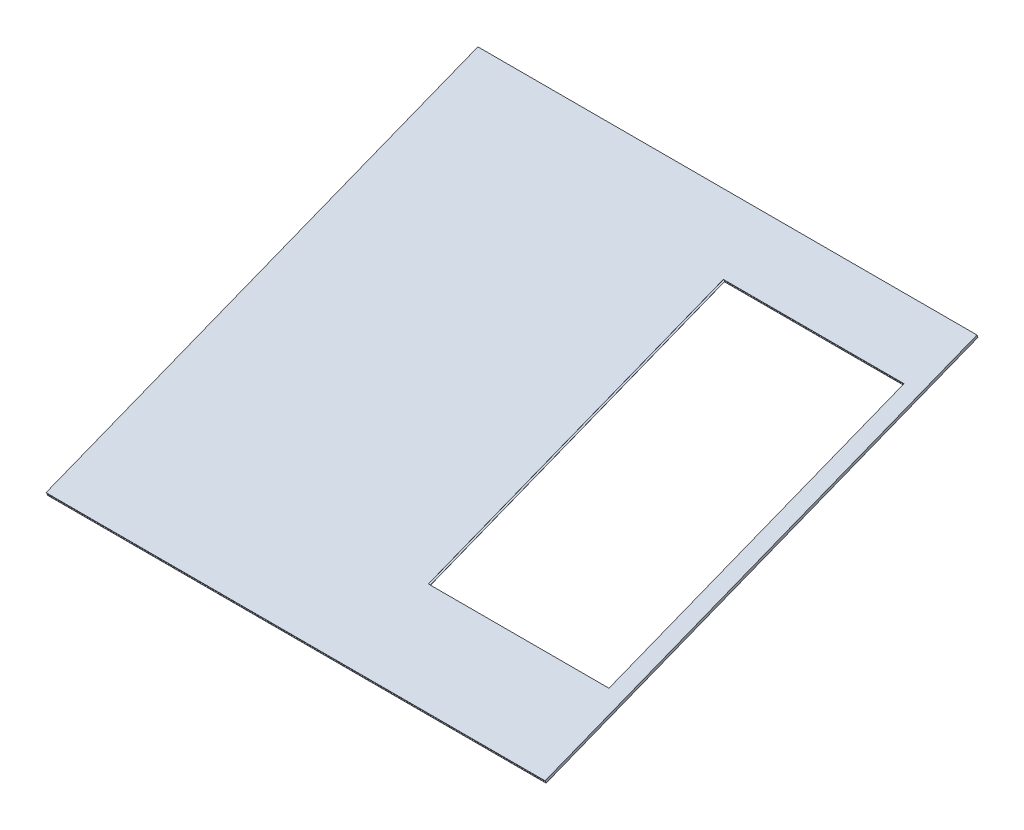
SolidWorks part; units mm, degrees
ref_plane "Front Plane" through (0, 0, 0) normal (0, 0, 1) x (1, 0, 0)
ref_plane "Top Plane" through (0, 0, 0) normal (0, 1, 0) x (1, 0, 0)
ref_plane "Right Plane" through (0, 0, 0) normal (1, 0, 0) x (0, 0, -1)
sketch "Sketch1" plane through (0, 0, 0) normal (1, 0, 0) x (0, 0, -1)
  line L0 (0, 0) -> (-1566.3458, 0) construction
  line L1 (0, 617) -> (-1566.3458, 0)
  line L2 (0, 0) -> (0, 617) construction
  dimension "D1" = 617
  dimension "D2" = 21.5
extrude "Extrude-Thin1" add sketch "Sketch1" along normal blind 1810 thin
sketch "Sketch2" plane through (0, 82.8774, -210.3965) normal (0, 0.3665, -0.9304) x (-1, 0, 0)
  line L0 (-1810, 584.0676) -> (-1810, 574.0676) construction
  line L1 (-1809.5, 583.5676) -> (-1800.5, 583.5676)
  line L2 (-1809.5, 583.5676) -> (-1809.5, 574.5676)
  line L3 (-1809.5, 574.5676) -> (-1800.5, 574.5676)
  line L4 (-1800.5, 583.5676) -> (-1800.5, 574.5676)
  line L5 (-1810, 584.0676) -> (0, 584.0676) construction
  line L6 (-1810, 574.0676) -> (0, 574.0676) construction
  line L7 (-1791, 583.5676) -> (-1791, 574.5676)
  line L8 (-1800, 574.5676) -> (-1791, 574.5676)
  line L9 (-1800, 583.5676) -> (-1800, 574.5676)
  line L10 (-1800, 583.5676) -> (-1791, 583.5676)
  line L11 (-1781.5, 583.5676) -> (-1781.5, 574.5676)
  line L12 (-1790.5, 574.5676) -> (-1781.5, 574.5676)
  line L13 (-1790.5, 583.5676) -> (-1790.5, 574.5676)
  line L14 (-1790.5, 583.5676) -> (-1781.5, 583.5676)
  line L15 (-1772, 583.5676) -> (-1772, 574.5676)
  line L16 (-1781, 574.5676) -> (-1772, 574.5676)
  line L17 (-1781, 583.5676) -> (-1781, 574.5676)
  line L18 (-1781, 583.5676) -> (-1772, 583.5676)
  line L19 (-1762.5, 583.5676) -> (-1762.5, 574.5676)
  line L20 (-1771.5, 574.5676) -> (-1762.5, 574.5676)
  line L21 (-1771.5, 583.5676) -> (-1771.5, 574.5676)
  line L22 (-1771.5, 583.5676) -> (-1762.5, 583.5676)
  line L23 (-1753, 583.5676) -> (-1753, 574.5676)
  line L24 (-1762, 574.5676) -> (-1753, 574.5676)
  line L25 (-1762, 583.5676) -> (-1762, 574.5676)
  line L26 (-1762, 583.5676) -> (-1753, 583.5676)
  line L27 (-1743.5, 583.5676) -> (-1743.5, 574.5676)
  line L28 (-1752.5, 574.5676) -> (-1743.5, 574.5676)
  line L29 (-1752.5, 583.5676) -> (-1752.5, 574.5676)
  line L30 (-1752.5, 583.5676) -> (-1743.5, 583.5676)
  line L31 (-1734, 583.5676) -> (-1734, 574.5676)
  line L32 (-1743, 574.5676) -> (-1734, 574.5676)
  line L33 (-1743, 583.5676) -> (-1743, 574.5676)
  line L34 (-1743, 583.5676) -> (-1734, 583.5676)
  line L35 (-1724.5, 583.5676) -> (-1724.5, 574.5676)
  line L36 (-1733.5, 574.5676) -> (-1724.5, 574.5676)
  line L37 (-1733.5, 583.5676) -> (-1733.5, 574.5676)
  line L38 (-1733.5, 583.5676) -> (-1724.5, 583.5676)
  line L39 (-1715, 583.5676) -> (-1715, 574.5676)
  line L40 (-1724, 574.5676) -> (-1715, 574.5676)
  line L41 (-1724, 583.5676) -> (-1724, 574.5676)
  line L42 (-1724, 583.5676) -> (-1715, 583.5676)
  line L43 (-1705.5, 583.5676) -> (-1705.5, 574.5676)
  line L44 (-1714.5, 574.5676) -> (-1705.5, 574.5676)
  line L45 (-1714.5, 583.5676) -> (-1714.5, 574.5676)
  line L46 (-1714.5, 583.5676) -> (-1705.5, 583.5676)
  line L47 (-1696, 583.5676) -> (-1696, 574.5676)
  line L48 (-1705, 574.5676) -> (-1696, 574.5676)
  line L49 (-1705, 583.5676) -> (-1705, 574.5676)
  line L50 (-1705, 583.5676) -> (-1696, 583.5676)
  line L51 (-1686.5, 583.5676) -> (-1686.5, 574.5676)
  line L52 (-1695.5, 574.5676) -> (-1686.5, 574.5676)
  line L53 (-1695.5, 583.5676) -> (-1695.5, 574.5676)
  line L54 (-1695.5, 583.5676) -> (-1686.5, 583.5676)
  line L55 (-1677, 583.5676) -> (-1677, 574.5676)
  line L56 (-1686, 574.5676) -> (-1677, 574.5676)
  line L57 (-1686, 583.5676) -> (-1686, 574.5676)
  line L58 (-1686, 583.5676) -> (-1677, 583.5676)
  line L59 (-1667.5, 583.5676) -> (-1667.5, 574.5676)
  line L60 (-1676.5, 574.5676) -> (-1667.5, 574.5676)
  line L61 (-1676.5, 583.5676) -> (-1676.5, 574.5676)
  line L62 (-1676.5, 583.5676) -> (-1667.5, 583.5676)
  line L63 (-1658, 583.5676) -> (-1658, 574.5676)
  line L64 (-1667, 574.5676) -> (-1658, 574.5676)
  line L65 (-1667, 583.5676) -> (-1667, 574.5676)
  line L66 (-1667, 583.5676) -> (-1658, 583.5676)
  line L67 (-1648.5, 583.5676) -> (-1648.5, 574.5676)
  line L68 (-1657.5, 574.5676) -> (-1648.5, 574.5676)
  line L69 (-1657.5, 583.5676) -> (-1657.5, 574.5676)
  line L70 (-1657.5, 583.5676) -> (-1648.5, 583.5676)
  line L71 (-1639, 583.5676) -> (-1639, 574.5676)
  line L72 (-1648, 574.5676) -> (-1639, 574.5676)
  line L73 (-1648, 583.5676) -> (-1648, 574.5676)
  line L74 (-1648, 583.5676) -> (-1639, 583.5676)
  line L75 (-1629.5, 583.5676) -> (-1629.5, 574.5676)
  line L76 (-1638.5, 574.5676) -> (-1629.5, 574.5676)
  line L77 (-1638.5, 583.5676) -> (-1638.5, 574.5676)
  line L78 (-1638.5, 583.5676) -> (-1629.5, 583.5676)
  line L79 (-1620, 583.5676) -> (-1620, 574.5676)
  line L80 (-1629, 574.5676) -> (-1620, 574.5676)
  line L81 (-1629, 583.5676) -> (-1629, 574.5676)
  line L82 (-1629, 583.5676) -> (-1620, 583.5676)
  line L83 (-1610.5, 583.5676) -> (-1610.5, 574.5676)
  line L84 (-1619.5, 574.5676) -> (-1610.5, 574.5676)
  line L85 (-1619.5, 583.5676) -> (-1619.5, 574.5676)
  line L86 (-1619.5, 583.5676) -> (-1610.5, 583.5676)
  line L87 (-1601, 583.5676) -> (-1601, 574.5676)
  line L88 (-1610, 574.5676) -> (-1601, 574.5676)
  line L89 (-1610, 583.5676) -> (-1610, 574.5676)
  line L90 (-1610, 583.5676) -> (-1601, 583.5676)
  line L91 (-1591.5, 583.5676) -> (-1591.5, 574.5676)
  line L92 (-1600.5, 574.5676) -> (-1591.5, 574.5676)
  line L93 (-1600.5, 583.5676) -> (-1600.5, 574.5676)
  line L94 (-1600.5, 583.5676) -> (-1591.5, 583.5676)
  line L95 (-1582, 583.5676) -> (-1582, 574.5676)
  line L96 (-1591, 574.5676) -> (-1582, 574.5676)
  line L97 (-1591, 583.5676) -> (-1591, 574.5676)
  line L98 (-1591, 583.5676) -> (-1582, 583.5676)
  line L99 (-1572.5, 583.5676) -> (-1572.5, 574.5676)
  line L100 (-1581.5, 574.5676) -> (-1572.5, 574.5676)
  line L101 (-1581.5, 583.5676) -> (-1581.5, 574.5676)
  line L102 (-1581.5, 583.5676) -> (-1572.5, 583.5676)
  line L103 (-1563, 583.5676) -> (-1563, 574.5676)
  line L104 (-1572, 574.5676) -> (-1563, 574.5676)
  line L105 (-1572, 583.5676) -> (-1572, 574.5676)
  line L106 (-1572, 583.5676) -> (-1563, 583.5676)
  line L107 (-1553.5, 583.5676) -> (-1553.5, 574.5676)
  line L108 (-1562.5, 574.5676) -> (-1553.5, 574.5676)
  line L109 (-1562.5, 583.5676) -> (-1562.5, 574.5676)
  line L110 (-1562.5, 583.5676) -> (-1553.5, 583.5676)
  line L111 (-1544, 583.5676) -> (-1544, 574.5676)
  line L112 (-1553, 574.5676) -> (-1544, 574.5676)
  line L113 (-1553, 583.5676) -> (-1553, 574.5676)
  line L114 (-1553, 583.5676) -> (-1544, 583.5676)
  line L115 (-1534.5, 583.5676) -> (-1534.5, 574.5676)
  line L116 (-1543.5, 574.5676) -> (-1534.5, 574.5676)
  line L117 (-1543.5, 583.5676) -> (-1543.5, 574.5676)
  line L118 (-1543.5, 583.5676) -> (-1534.5, 583.5676)
  line L119 (-1525, 583.5676) -> (-1525, 574.5676)
  line L120 (-1534, 574.5676) -> (-1525, 574.5676)
  line L121 (-1534, 583.5676) -> (-1534, 574.5676)
  line L122 (-1534, 583.5676) -> (-1525, 583.5676)
  line L123 (-1515.5, 583.5676) -> (-1515.5, 574.5676)
  line L124 (-1524.5, 574.5676) -> (-1515.5, 574.5676)
  line L125 (-1524.5, 583.5676) -> (-1524.5, 574.5676)
  line L126 (-1524.5, 583.5676) -> (-1515.5, 583.5676)
  line L127 (-1506, 583.5676) -> (-1506, 574.5676)
  line L128 (-1515, 574.5676) -> (-1506, 574.5676)
  line L129 (-1515, 583.5676) -> (-1515, 574.5676)
  line L130 (-1515, 583.5676) -> (-1506, 583.5676)
  line L131 (-1496.5, 583.5676) -> (-1496.5, 574.5676)
  line L132 (-1505.5, 574.5676) -> (-1496.5, 574.5676)
  line L133 (-1505.5, 583.5676) -> (-1505.5, 574.5676)
  line L134 (-1505.5, 583.5676) -> (-1496.5, 583.5676)
  line L135 (-1487, 583.5676) -> (-1487, 574.5676)
  line L136 (-1496, 574.5676) -> (-1487, 574.5676)
  line L137 (-1496, 583.5676) -> (-1496, 574.5676)
  line L138 (-1496, 583.5676) -> (-1487, 583.5676)
  line L139 (-1477.5, 583.5676) -> (-1477.5, 574.5676)
  line L140 (-1486.5, 574.5676) -> (-1477.5, 574.5676)
  line L141 (-1486.5, 583.5676) -> (-1486.5, 574.5676)
  line L142 (-1486.5, 583.5676) -> (-1477.5, 583.5676)
  line L143 (-1468, 583.5676) -> (-1468, 574.5676)
  line L144 (-1477, 574.5676) -> (-1468, 574.5676)
  line L145 (-1477, 583.5676) -> (-1477, 574.5676)
  line L146 (-1477, 583.5676) -> (-1468, 583.5676)
  line L147 (-1458.5, 583.5676) -> (-1458.5, 574.5676)
  line L148 (-1467.5, 574.5676) -> (-1458.5, 574.5676)
  line L149 (-1467.5, 583.5676) -> (-1467.5, 574.5676)
  line L150 (-1467.5, 583.5676) -> (-1458.5, 583.5676)
  line L151 (-1449, 583.5676) -> (-1449, 574.5676)
  line L152 (-1458, 574.5676) -> (-1449, 574.5676)
  line L153 (-1458, 583.5676) -> (-1458, 574.5676)
  line L154 (-1458, 583.5676) -> (-1449, 583.5676)
  line L155 (-1439.5, 583.5676) -> (-1439.5, 574.5676)
  line L156 (-1448.5, 574.5676) -> (-1439.5, 574.5676)
  line L157 (-1448.5, 583.5676) -> (-1448.5, 574.5676)
  line L158 (-1448.5, 583.5676) -> (-1439.5, 583.5676)
  line L159 (-1430, 583.5676) -> (-1430, 574.5676)
  line L160 (-1439, 574.5676) -> (-1430, 574.5676)
  line L161 (-1439, 583.5676) -> (-1439, 574.5676)
  line L162 (-1439, 583.5676) -> (-1430, 583.5676)
  line L163 (-1420.5, 583.5676) -> (-1420.5, 574.5676)
  line L164 (-1429.5, 574.5676) -> (-1420.5, 574.5676)
  line L165 (-1429.5, 583.5676) -> (-1429.5, 574.5676)
  line L166 (-1429.5, 583.5676) -> (-1420.5, 583.5676)
  line L167 (-1411, 583.5676) -> (-1411, 574.5676)
  line L168 (-1420, 574.5676) -> (-1411, 574.5676)
  line L169 (-1420, 583.5676) -> (-1420, 574.5676)
  line L170 (-1420, 583.5676) -> (-1411, 583.5676)
  line L171 (-1401.5, 583.5676) -> (-1401.5, 574.5676)
  line L172 (-1410.5, 574.5676) -> (-1401.5, 574.5676)
  line L173 (-1410.5, 583.5676) -> (-1410.5, 574.5676)
  line L174 (-1410.5, 583.5676) -> (-1401.5, 583.5676)
  line L175 (-1392, 583.5676) -> (-1392, 574.5676)
  line L176 (-1401, 574.5676) -> (-1392, 574.5676)
  line L177 (-1401, 583.5676) -> (-1401, 574.5676)
  line L178 (-1401, 583.5676) -> (-1392, 583.5676)
  line L179 (-1382.5, 583.5676) -> (-1382.5, 574.5676)
  line L180 (-1391.5, 574.5676) -> (-1382.5, 574.5676)
  line L181 (-1391.5, 583.5676) -> (-1391.5, 574.5676)
  line L182 (-1391.5, 583.5676) -> (-1382.5, 583.5676)
  line L183 (-1373, 583.5676) -> (-1373, 574.5676)
  line L184 (-1382, 574.5676) -> (-1373, 574.5676)
  line L185 (-1382, 583.5676) -> (-1382, 574.5676)
  line L186 (-1382, 583.5676) -> (-1373, 583.5676)
  line L187 (-1363.5, 583.5676) -> (-1363.5, 574.5676)
  line L188 (-1372.5, 574.5676) -> (-1363.5, 574.5676)
  line L189 (-1372.5, 583.5676) -> (-1372.5, 574.5676)
  line L190 (-1372.5, 583.5676) -> (-1363.5, 583.5676)
  line L191 (-1354, 583.5676) -> (-1354, 574.5676)
  line L192 (-1363, 574.5676) -> (-1354, 574.5676)
  line L193 (-1363, 583.5676) -> (-1363, 574.5676)
  line L194 (-1363, 583.5676) -> (-1354, 583.5676)
  line L195 (-1344.5, 583.5676) -> (-1344.5, 574.5676)
  line L196 (-1353.5, 574.5676) -> (-1344.5, 574.5676)
  line L197 (-1353.5, 583.5676) -> (-1353.5, 574.5676)
  line L198 (-1353.5, 583.5676) -> (-1344.5, 583.5676)
  line L199 (-1335, 583.5676) -> (-1335, 574.5676)
  line L200 (-1344, 574.5676) -> (-1335, 574.5676)
  line L201 (-1344, 583.5676) -> (-1344, 574.5676)
  line L202 (-1344, 583.5676) -> (-1335, 583.5676)
  line L203 (-1325.5, 583.5676) -> (-1325.5, 574.5676)
  line L204 (-1334.5, 574.5676) -> (-1325.5, 574.5676)
  line L205 (-1334.5, 583.5676) -> (-1334.5, 574.5676)
  line L206 (-1334.5, 583.5676) -> (-1325.5, 583.5676)
  line L207 (-1316, 583.5676) -> (-1316, 574.5676)
  line L208 (-1325, 574.5676) -> (-1316, 574.5676)
  line L209 (-1325, 583.5676) -> (-1325, 574.5676)
  line L210 (-1325, 583.5676) -> (-1316, 583.5676)
  line L211 (-1306.5, 583.5676) -> (-1306.5, 574.5676)
  line L212 (-1315.5, 574.5676) -> (-1306.5, 574.5676)
  line L213 (-1315.5, 583.5676) -> (-1315.5, 574.5676)
  line L214 (-1315.5, 583.5676) -> (-1306.5, 583.5676)
  line L215 (-1297, 583.5676) -> (-1297, 574.5676)
  line L216 (-1306, 574.5676) -> (-1297, 574.5676)
  line L217 (-1306, 583.5676) -> (-1306, 574.5676)
  line L218 (-1306, 583.5676) -> (-1297, 583.5676)
  line L219 (-1287.5, 583.5676) -> (-1287.5, 574.5676)
  line L220 (-1296.5, 574.5676) -> (-1287.5, 574.5676)
  line L221 (-1296.5, 583.5676) -> (-1296.5, 574.5676)
  line L222 (-1296.5, 583.5676) -> (-1287.5, 583.5676)
  line L223 (-1278, 583.5676) -> (-1278, 574.5676)
  line L224 (-1287, 574.5676) -> (-1278, 574.5676)
  line L225 (-1287, 583.5676) -> (-1287, 574.5676)
  line L226 (-1287, 583.5676) -> (-1278, 583.5676)
  line L227 (-1268.5, 583.5676) -> (-1268.5, 574.5676)
  line L228 (-1277.5, 574.5676) -> (-1268.5, 574.5676)
  line L229 (-1277.5, 583.5676) -> (-1277.5, 574.5676)
  line L230 (-1277.5, 583.5676) -> (-1268.5, 583.5676)
  line L231 (-1259, 583.5676) -> (-1259, 574.5676)
  line L232 (-1268, 574.5676) -> (-1259, 574.5676)
  line L233 (-1268, 583.5676) -> (-1268, 574.5676)
  line L234 (-1268, 583.5676) -> (-1259, 583.5676)
  line L235 (-1249.5, 583.5676) -> (-1249.5, 574.5676)
  line L236 (-1258.5, 574.5676) -> (-1249.5, 574.5676)
  line L237 (-1258.5, 583.5676) -> (-1258.5, 574.5676)
  line L238 (-1258.5, 583.5676) -> (-1249.5, 583.5676)
  line L239 (-1240, 583.5676) -> (-1240, 574.5676)
  line L240 (-1249, 574.5676) -> (-1240, 574.5676)
  line L241 (-1249, 583.5676) -> (-1249, 574.5676)
  line L242 (-1249, 583.5676) -> (-1240, 583.5676)
  line L243 (-1230.5, 583.5676) -> (-1230.5, 574.5676)
  line L244 (-1239.5, 574.5676) -> (-1230.5, 574.5676)
  line L245 (-1239.5, 583.5676) -> (-1239.5, 574.5676)
  line L246 (-1239.5, 583.5676) -> (-1230.5, 583.5676)
  line L247 (-1221, 583.5676) -> (-1221, 574.5676)
  line L248 (-1230, 574.5676) -> (-1221, 574.5676)
  line L249 (-1230, 583.5676) -> (-1230, 574.5676)
  line L250 (-1230, 583.5676) -> (-1221, 583.5676)
  line L251 (-1211.5, 583.5676) -> (-1211.5, 574.5676)
  line L252 (-1220.5, 574.5676) -> (-1211.5, 574.5676)
  line L253 (-1220.5, 583.5676) -> (-1220.5, 574.5676)
  line L254 (-1220.5, 583.5676) -> (-1211.5, 583.5676)
  line L255 (-1202, 583.5676) -> (-1202, 574.5676)
  line L256 (-1211, 574.5676) -> (-1202, 574.5676)
  line L257 (-1211, 583.5676) -> (-1211, 574.5676)
  line L258 (-1211, 583.5676) -> (-1202, 583.5676)
  line L259 (-1192.5, 583.5676) -> (-1192.5, 574.5676)
  line L260 (-1201.5, 574.5676) -> (-1192.5, 574.5676)
  line L261 (-1201.5, 583.5676) -> (-1201.5, 574.5676)
  line L262 (-1201.5, 583.5676) -> (-1192.5, 583.5676)
  line L263 (-1183, 583.5676) -> (-1183, 574.5676)
  line L264 (-1192, 574.5676) -> (-1183, 574.5676)
  line L265 (-1192, 583.5676) -> (-1192, 574.5676)
  line L266 (-1192, 583.5676) -> (-1183, 583.5676)
  line L267 (-1173.5, 583.5676) -> (-1173.5, 574.5676)
  line L268 (-1182.5, 574.5676) -> (-1173.5, 574.5676)
  line L269 (-1182.5, 583.5676) -> (-1182.5, 574.5676)
  line L270 (-1182.5, 583.5676) -> (-1173.5, 583.5676)
  line L271 (-1164, 583.5676) -> (-1164, 574.5676)
  line L272 (-1173, 574.5676) -> (-1164, 574.5676)
  line L273 (-1173, 583.5676) -> (-1173, 574.5676)
  line L274 (-1173, 583.5676) -> (-1164, 583.5676)
  line L275 (-1154.5, 583.5676) -> (-1154.5, 574.5676)
  line L276 (-1163.5, 574.5676) -> (-1154.5, 574.5676)
  line L277 (-1163.5, 583.5676) -> (-1163.5, 574.5676)
  line L278 (-1163.5, 583.5676) -> (-1154.5, 583.5676)
  line L279 (-1145, 583.5676) -> (-1145, 574.5676)
  line L280 (-1154, 574.5676) -> (-1145, 574.5676)
  line L281 (-1154, 583.5676) -> (-1154, 574.5676)
  line L282 (-1154, 583.5676) -> (-1145, 583.5676)
  line L283 (-1135.5, 583.5676) -> (-1135.5, 574.5676)
  line L284 (-1144.5, 574.5676) -> (-1135.5, 574.5676)
  line L285 (-1144.5, 583.5676) -> (-1144.5, 574.5676)
  line L286 (-1144.5, 583.5676) -> (-1135.5, 583.5676)
  line L287 (-1126, 583.5676) -> (-1126, 574.5676)
  line L288 (-1135, 574.5676) -> (-1126, 574.5676)
  line L289 (-1135, 583.5676) -> (-1135, 574.5676)
  line L290 (-1135, 583.5676) -> (-1126, 583.5676)
  line L291 (-1116.5, 583.5676) -> (-1116.5, 574.5676)
  line L292 (-1125.5, 574.5676) -> (-1116.5, 574.5676)
  line L293 (-1125.5, 583.5676) -> (-1125.5, 574.5676)
  line L294 (-1125.5, 583.5676) -> (-1116.5, 583.5676)
  line L295 (-1107, 583.5676) -> (-1107, 574.5676)
  line L296 (-1116, 574.5676) -> (-1107, 574.5676)
  line L297 (-1116, 583.5676) -> (-1116, 574.5676)
  line L298 (-1116, 583.5676) -> (-1107, 583.5676)
  line L299 (-1097.5, 583.5676) -> (-1097.5, 574.5676)
  line L300 (-1106.5, 574.5676) -> (-1097.5, 574.5676)
  line L301 (-1106.5, 583.5676) -> (-1106.5, 574.5676)
  line L302 (-1106.5, 583.5676) -> (-1097.5, 583.5676)
  line L303 (-1088, 583.5676) -> (-1088, 574.5676)
  line L304 (-1097, 574.5676) -> (-1088, 574.5676)
  line L305 (-1097, 583.5676) -> (-1097, 574.5676)
  line L306 (-1097, 583.5676) -> (-1088, 583.5676)
  line L307 (-1078.5, 583.5676) -> (-1078.5, 574.5676)
  line L308 (-1087.5, 574.5676) -> (-1078.5, 574.5676)
  line L309 (-1087.5, 583.5676) -> (-1087.5, 574.5676)
  line L310 (-1087.5, 583.5676) -> (-1078.5, 583.5676)
  line L311 (-1069, 583.5676) -> (-1069, 574.5676)
  line L312 (-1078, 574.5676) -> (-1069, 574.5676)
  line L313 (-1078, 583.5676) -> (-1078, 574.5676)
  line L314 (-1078, 583.5676) -> (-1069, 583.5676)
  line L315 (-1059.5, 583.5676) -> (-1059.5, 574.5676)
  line L316 (-1068.5, 574.5676) -> (-1059.5, 574.5676)
  line L317 (-1068.5, 583.5676) -> (-1068.5, 574.5676)
  line L318 (-1068.5, 583.5676) -> (-1059.5, 583.5676)
  line L319 (-1050, 583.5676) -> (-1050, 574.5676)
  line L320 (-1059, 574.5676) -> (-1050, 574.5676)
  line L321 (-1059, 583.5676) -> (-1059, 574.5676)
  line L322 (-1059, 583.5676) -> (-1050, 583.5676)
  line L323 (-1040.5, 583.5676) -> (-1040.5, 574.5676)
  line L324 (-1049.5, 574.5676) -> (-1040.5, 574.5676)
  line L325 (-1049.5, 583.5676) -> (-1049.5, 574.5676)
  line L326 (-1049.5, 583.5676) -> (-1040.5, 583.5676)
  line L327 (-1031, 583.5676) -> (-1031, 574.5676)
  line L328 (-1040, 574.5676) -> (-1031, 574.5676)
  line L329 (-1040, 583.5676) -> (-1040, 574.5676)
  line L330 (-1040, 583.5676) -> (-1031, 583.5676)
  line L331 (-1021.5, 583.5676) -> (-1021.5, 574.5676)
  line L332 (-1030.5, 574.5676) -> (-1021.5, 574.5676)
  line L333 (-1030.5, 583.5676) -> (-1030.5, 574.5676)
  line L334 (-1030.5, 583.5676) -> (-1021.5, 583.5676)
  line L335 (-1012, 583.5676) -> (-1012, 574.5676)
  line L336 (-1021, 574.5676) -> (-1012, 574.5676)
  line L337 (-1021, 583.5676) -> (-1021, 574.5676)
  line L338 (-1021, 583.5676) -> (-1012, 583.5676)
  line L339 (-1002.5, 583.5676) -> (-1002.5, 574.5676)
  line L340 (-1011.5, 574.5676) -> (-1002.5, 574.5676)
  line L341 (-1011.5, 583.5676) -> (-1011.5, 574.5676)
  line L342 (-1011.5, 583.5676) -> (-1002.5, 583.5676)
  line L343 (-993, 583.5676) -> (-993, 574.5676)
  line L344 (-1002, 574.5676) -> (-993, 574.5676)
  line L345 (-1002, 583.5676) -> (-1002, 574.5676)
  line L346 (-1002, 583.5676) -> (-993, 583.5676)
  line L347 (-983.5, 583.5676) -> (-983.5, 574.5676)
  line L348 (-992.5, 574.5676) -> (-983.5, 574.5676)
  line L349 (-992.5, 583.5676) -> (-992.5, 574.5676)
  line L350 (-992.5, 583.5676) -> (-983.5, 583.5676)
  line L351 (-974, 583.5676) -> (-974, 574.5676)
  line L352 (-983, 574.5676) -> (-974, 574.5676)
  line L353 (-983, 583.5676) -> (-983, 574.5676)
  line L354 (-983, 583.5676) -> (-974, 583.5676)
  line L355 (-964.5, 583.5676) -> (-964.5, 574.5676)
  line L356 (-973.5, 574.5676) -> (-964.5, 574.5676)
  line L357 (-973.5, 583.5676) -> (-973.5, 574.5676)
  line L358 (-973.5, 583.5676) -> (-964.5, 583.5676)
  line L359 (-955, 583.5676) -> (-955, 574.5676)
  line L360 (-964, 574.5676) -> (-955, 574.5676)
  line L361 (-964, 583.5676) -> (-964, 574.5676)
  line L362 (-964, 583.5676) -> (-955, 583.5676)
  line L363 (-945.5, 583.5676) -> (-945.5, 574.5676)
  line L364 (-954.5, 574.5676) -> (-945.5, 574.5676)
  line L365 (-954.5, 583.5676) -> (-954.5, 574.5676)
  line L366 (-954.5, 583.5676) -> (-945.5, 583.5676)
  line L367 (-936, 583.5676) -> (-936, 574.5676)
  line L368 (-945, 574.5676) -> (-936, 574.5676)
  line L369 (-945, 583.5676) -> (-945, 574.5676)
  line L370 (-945, 583.5676) -> (-936, 583.5676)
  line L371 (-926.5, 583.5676) -> (-926.5, 574.5676)
  line L372 (-935.5, 574.5676) -> (-926.5, 574.5676)
  line L373 (-935.5, 583.5676) -> (-935.5, 574.5676)
  line L374 (-935.5, 583.5676) -> (-926.5, 583.5676)
  line L375 (-917, 583.5676) -> (-917, 574.5676)
  line L376 (-926, 574.5676) -> (-917, 574.5676)
  line L377 (-926, 583.5676) -> (-926, 574.5676)
  line L378 (-926, 583.5676) -> (-917, 583.5676)
  line L379 (-907.5, 583.5676) -> (-907.5, 574.5676)
  line L380 (-916.5, 574.5676) -> (-907.5, 574.5676)
  line L381 (-916.5, 583.5676) -> (-916.5, 574.5676)
  line L382 (-916.5, 583.5676) -> (-907.5, 583.5676)
  line L383 (-898, 583.5676) -> (-898, 574.5676)
  line L384 (-907, 574.5676) -> (-898, 574.5676)
  line L385 (-907, 583.5676) -> (-907, 574.5676)
  line L386 (-907, 583.5676) -> (-898, 583.5676)
  line L387 (-888.5, 583.5676) -> (-888.5, 574.5676)
  line L388 (-897.5, 574.5676) -> (-888.5, 574.5676)
  line L389 (-897.5, 583.5676) -> (-897.5, 574.5676)
  line L390 (-897.5, 583.5676) -> (-888.5, 583.5676)
  line L391 (-879, 583.5676) -> (-879, 574.5676)
  line L392 (-888, 574.5676) -> (-879, 574.5676)
  line L393 (-888, 583.5676) -> (-888, 574.5676)
  line L394 (-888, 583.5676) -> (-879, 583.5676)
  line L395 (-869.5, 583.5676) -> (-869.5, 574.5676)
  line L396 (-878.5, 574.5676) -> (-869.5, 574.5676)
  line L397 (-878.5, 583.5676) -> (-878.5, 574.5676)
  line L398 (-878.5, 583.5676) -> (-869.5, 583.5676)
  line L399 (-860, 583.5676) -> (-860, 574.5676)
  line L400 (-869, 574.5676) -> (-860, 574.5676)
  line L401 (-869, 583.5676) -> (-869, 574.5676)
  line L402 (-869, 583.5676) -> (-860, 583.5676)
  line L403 (-850.5, 583.5676) -> (-850.5, 574.5676)
  line L404 (-859.5, 574.5676) -> (-850.5, 574.5676)
  line L405 (-859.5, 583.5676) -> (-859.5, 574.5676)
  line L406 (-859.5, 583.5676) -> (-850.5, 583.5676)
  line L407 (-841, 583.5676) -> (-841, 574.5676)
  line L408 (-850, 574.5676) -> (-841, 574.5676)
  line L409 (-850, 583.5676) -> (-850, 574.5676)
  line L410 (-850, 583.5676) -> (-841, 583.5676)
  line L411 (-831.5, 583.5676) -> (-831.5, 574.5676)
  line L412 (-840.5, 574.5676) -> (-831.5, 574.5676)
  line L413 (-840.5, 583.5676) -> (-840.5, 574.5676)
  line L414 (-840.5, 583.5676) -> (-831.5, 583.5676)
  line L415 (-822, 583.5676) -> (-822, 574.5676)
  line L416 (-831, 574.5676) -> (-822, 574.5676)
  line L417 (-831, 583.5676) -> (-831, 574.5676)
  line L418 (-831, 583.5676) -> (-822, 583.5676)
  line L419 (-812.5, 583.5676) -> (-812.5, 574.5676)
  line L420 (-821.5, 574.5676) -> (-812.5, 574.5676)
  line L421 (-821.5, 583.5676) -> (-821.5, 574.5676)
  line L422 (-821.5, 583.5676) -> (-812.5, 583.5676)
  line L423 (-803, 583.5676) -> (-803, 574.5676)
  line L424 (-812, 574.5676) -> (-803, 574.5676)
  line L425 (-812, 583.5676) -> (-812, 574.5676)
  line L426 (-812, 583.5676) -> (-803, 583.5676)
  line L427 (-793.5, 583.5676) -> (-793.5, 574.5676)
  line L428 (-802.5, 574.5676) -> (-793.5, 574.5676)
  line L429 (-802.5, 583.5676) -> (-802.5, 574.5676)
  line L430 (-802.5, 583.5676) -> (-793.5, 583.5676)
  line L431 (-784, 583.5676) -> (-784, 574.5676)
  line L432 (-793, 574.5676) -> (-784, 574.5676)
  line L433 (-793, 583.5676) -> (-793, 574.5676)
  line L434 (-793, 583.5676) -> (-784, 583.5676)
  line L435 (-774.5, 583.5676) -> (-774.5, 574.5676)
  line L436 (-783.5, 574.5676) -> (-774.5, 574.5676)
  line L437 (-783.5, 583.5676) -> (-783.5, 574.5676)
  line L438 (-783.5, 583.5676) -> (-774.5, 583.5676)
  line L439 (-765, 583.5676) -> (-765, 574.5676)
  line L440 (-774, 574.5676) -> (-765, 574.5676)
  line L441 (-774, 583.5676) -> (-774, 574.5676)
  line L442 (-774, 583.5676) -> (-765, 583.5676)
  line L443 (-755.5, 583.5676) -> (-755.5, 574.5676)
  line L444 (-764.5, 574.5676) -> (-755.5, 574.5676)
  line L445 (-764.5, 583.5676) -> (-764.5, 574.5676)
  line L446 (-764.5, 583.5676) -> (-755.5, 583.5676)
  line L447 (-746, 583.5676) -> (-746, 574.5676)
  line L448 (-755, 574.5676) -> (-746, 574.5676)
  line L449 (-755, 583.5676) -> (-755, 574.5676)
  line L450 (-755, 583.5676) -> (-746, 583.5676)
  line L451 (-736.5, 583.5676) -> (-736.5, 574.5676)
  line L452 (-745.5, 574.5676) -> (-736.5, 574.5676)
  line L453 (-745.5, 583.5676) -> (-745.5, 574.5676)
  line L454 (-745.5, 583.5676) -> (-736.5, 583.5676)
  line L455 (-727, 583.5676) -> (-727, 574.5676)
  line L456 (-736, 574.5676) -> (-727, 574.5676)
  line L457 (-736, 583.5676) -> (-736, 574.5676)
  line L458 (-736, 583.5676) -> (-727, 583.5676)
  line L459 (-717.5, 583.5676) -> (-717.5, 574.5676)
  line L460 (-726.5, 574.5676) -> (-717.5, 574.5676)
  line L461 (-726.5, 583.5676) -> (-726.5, 574.5676)
  line L462 (-726.5, 583.5676) -> (-717.5, 583.5676)
  line L463 (-708, 583.5676) -> (-708, 574.5676)
  line L464 (-717, 574.5676) -> (-708, 574.5676)
  line L465 (-717, 583.5676) -> (-717, 574.5676)
  line L466 (-717, 583.5676) -> (-708, 583.5676)
  line L467 (-698.5, 583.5676) -> (-698.5, 574.5676)
  line L468 (-707.5, 574.5676) -> (-698.5, 574.5676)
  line L469 (-707.5, 583.5676) -> (-707.5, 574.5676)
  line L470 (-707.5, 583.5676) -> (-698.5, 583.5676)
  line L471 (-689, 583.5676) -> (-689, 574.5676)
  line L472 (-698, 574.5676) -> (-689, 574.5676)
  line L473 (-698, 583.5676) -> (-698, 574.5676)
  line L474 (-698, 583.5676) -> (-689, 583.5676)
  line L475 (-679.5, 583.5676) -> (-679.5, 574.5676)
  line L476 (-688.5, 574.5676) -> (-679.5, 574.5676)
  line L477 (-688.5, 583.5676) -> (-688.5, 574.5676)
  line L478 (-688.5, 583.5676) -> (-679.5, 583.5676)
  line L479 (-670, 583.5676) -> (-670, 574.5676)
  line L480 (-679, 574.5676) -> (-670, 574.5676)
  line L481 (-679, 583.5676) -> (-679, 574.5676)
  line L482 (-679, 583.5676) -> (-670, 583.5676)
  line L483 (-660.5, 583.5676) -> (-660.5, 574.5676)
  line L484 (-669.5, 574.5676) -> (-660.5, 574.5676)
  line L485 (-669.5, 583.5676) -> (-669.5, 574.5676)
  line L486 (-669.5, 583.5676) -> (-660.5, 583.5676)
  line L487 (-651, 583.5676) -> (-651, 574.5676)
  line L488 (-660, 574.5676) -> (-651, 574.5676)
  line L489 (-660, 583.5676) -> (-660, 574.5676)
  line L490 (-660, 583.5676) -> (-651, 583.5676)
  line L491 (-641.5, 583.5676) -> (-641.5, 574.5676)
  line L492 (-650.5, 574.5676) -> (-641.5, 574.5676)
  line L493 (-650.5, 583.5676) -> (-650.5, 574.5676)
  line L494 (-650.5, 583.5676) -> (-641.5, 583.5676)
  line L495 (-632, 583.5676) -> (-632, 574.5676)
  line L496 (-641, 574.5676) -> (-632, 574.5676)
  line L497 (-641, 583.5676) -> (-641, 574.5676)
  line L498 (-641, 583.5676) -> (-632, 583.5676)
  line L499 (-622.5, 583.5676) -> (-622.5, 574.5676)
  line L500 (-631.5, 574.5676) -> (-622.5, 574.5676)
  line L501 (-631.5, 583.5676) -> (-631.5, 574.5676)
  line L502 (-631.5, 583.5676) -> (-622.5, 583.5676)
  line L503 (-613, 583.5676) -> (-613, 574.5676)
  line L504 (-622, 574.5676) -> (-613, 574.5676)
  line L505 (-622, 583.5676) -> (-622, 574.5676)
  line L506 (-622, 583.5676) -> (-613, 583.5676)
  line L507 (-603.5, 583.5676) -> (-603.5, 574.5676)
  line L508 (-612.5, 574.5676) -> (-603.5, 574.5676)
  line L509 (-612.5, 583.5676) -> (-612.5, 574.5676)
  line L510 (-612.5, 583.5676) -> (-603.5, 583.5676)
  line L511 (-594, 583.5676) -> (-594, 574.5676)
  line L512 (-603, 574.5676) -> (-594, 574.5676)
  line L513 (-603, 583.5676) -> (-603, 574.5676)
  line L514 (-603, 583.5676) -> (-594, 583.5676)
  line L515 (-584.5, 583.5676) -> (-584.5, 574.5676)
  line L516 (-593.5, 574.5676) -> (-584.5, 574.5676)
  line L517 (-593.5, 583.5676) -> (-593.5, 574.5676)
  line L518 (-593.5, 583.5676) -> (-584.5, 583.5676)
  line L519 (-575, 583.5676) -> (-575, 574.5676)
  line L520 (-584, 574.5676) -> (-575, 574.5676)
  line L521 (-584, 583.5676) -> (-584, 574.5676)
  line L522 (-584, 583.5676) -> (-575, 583.5676)
  line L523 (-565.5, 583.5676) -> (-565.5, 574.5676)
  line L524 (-574.5, 574.5676) -> (-565.5, 574.5676)
  line L525 (-574.5, 583.5676) -> (-574.5, 574.5676)
  line L526 (-574.5, 583.5676) -> (-565.5, 583.5676)
  line L527 (-556, 583.5676) -> (-556, 574.5676)
  line L528 (-565, 574.5676) -> (-556, 574.5676)
  line L529 (-565, 583.5676) -> (-565, 574.5676)
  line L530 (-565, 583.5676) -> (-556, 583.5676)
  line L531 (-546.5, 583.5676) -> (-546.5, 574.5676)
  line L532 (-555.5, 574.5676) -> (-546.5, 574.5676)
  line L533 (-555.5, 583.5676) -> (-555.5, 574.5676)
  line L534 (-555.5, 583.5676) -> (-546.5, 583.5676)
  line L535 (-537, 583.5676) -> (-537, 574.5676)
  line L536 (-546, 574.5676) -> (-537, 574.5676)
  line L537 (-546, 583.5676) -> (-546, 574.5676)
  line L538 (-546, 583.5676) -> (-537, 583.5676)
  line L539 (-527.5, 583.5676) -> (-527.5, 574.5676)
  line L540 (-536.5, 574.5676) -> (-527.5, 574.5676)
  line L541 (-536.5, 583.5676) -> (-536.5, 574.5676)
  line L542 (-536.5, 583.5676) -> (-527.5, 583.5676)
  line L543 (-518, 583.5676) -> (-518, 574.5676)
  line L544 (-527, 574.5676) -> (-518, 574.5676)
  line L545 (-527, 583.5676) -> (-527, 574.5676)
  line L546 (-527, 583.5676) -> (-518, 583.5676)
  line L547 (-508.5, 583.5676) -> (-508.5, 574.5676)
  line L548 (-517.5, 574.5676) -> (-508.5, 574.5676)
  line L549 (-517.5, 583.5676) -> (-517.5, 574.5676)
  line L550 (-517.5, 583.5676) -> (-508.5, 583.5676)
  line L551 (-499, 583.5676) -> (-499, 574.5676)
  line L552 (-508, 574.5676) -> (-499, 574.5676)
  line L553 (-508, 583.5676) -> (-508, 574.5676)
  line L554 (-508, 583.5676) -> (-499, 583.5676)
  line L555 (-489.5, 583.5676) -> (-489.5, 574.5676)
  line L556 (-498.5, 574.5676) -> (-489.5, 574.5676)
  line L557 (-498.5, 583.5676) -> (-498.5, 574.5676)
  line L558 (-498.5, 583.5676) -> (-489.5, 583.5676)
  line L559 (-480, 583.5676) -> (-480, 574.5676)
  line L560 (-489, 574.5676) -> (-480, 574.5676)
  line L561 (-489, 583.5676) -> (-489, 574.5676)
  line L562 (-489, 583.5676) -> (-480, 583.5676)
  line L563 (-470.5, 583.5676) -> (-470.5, 574.5676)
  line L564 (-479.5, 574.5676) -> (-470.5, 574.5676)
  line L565 (-479.5, 583.5676) -> (-479.5, 574.5676)
  line L566 (-479.5, 583.5676) -> (-470.5, 583.5676)
  line L567 (-461, 583.5676) -> (-461, 574.5676)
  line L568 (-470, 574.5676) -> (-461, 574.5676)
  line L569 (-470, 583.5676) -> (-470, 574.5676)
  line L570 (-470, 583.5676) -> (-461, 583.5676)
  line L571 (-451.5, 583.5676) -> (-451.5, 574.5676)
  line L572 (-460.5, 574.5676) -> (-451.5, 574.5676)
  line L573 (-460.5, 583.5676) -> (-460.5, 574.5676)
  line L574 (-460.5, 583.5676) -> (-451.5, 583.5676)
  line L575 (-442, 583.5676) -> (-442, 574.5676)
  line L576 (-451, 574.5676) -> (-442, 574.5676)
  line L577 (-451, 583.5676) -> (-451, 574.5676)
  line L578 (-451, 583.5676) -> (-442, 583.5676)
  line L579 (-432.5, 583.5676) -> (-432.5, 574.5676)
  line L580 (-441.5, 574.5676) -> (-432.5, 574.5676)
  line L581 (-441.5, 583.5676) -> (-441.5, 574.5676)
  line L582 (-441.5, 583.5676) -> (-432.5, 583.5676)
  line L583 (-423, 583.5676) -> (-423, 574.5676)
  line L584 (-432, 574.5676) -> (-423, 574.5676)
  line L585 (-432, 583.5676) -> (-432, 574.5676)
  line L586 (-432, 583.5676) -> (-423, 583.5676)
  line L587 (-413.5, 583.5676) -> (-413.5, 574.5676)
  line L588 (-422.5, 574.5676) -> (-413.5, 574.5676)
  line L589 (-422.5, 583.5676) -> (-422.5, 574.5676)
  line L590 (-422.5, 583.5676) -> (-413.5, 583.5676)
  line L591 (-404, 583.5676) -> (-404, 574.5676)
  line L592 (-413, 574.5676) -> (-404, 574.5676)
  line L593 (-413, 583.5676) -> (-413, 574.5676)
  line L594 (-413, 583.5676) -> (-404, 583.5676)
  line L595 (-394.5, 583.5676) -> (-394.5, 574.5676)
  line L596 (-403.5, 574.5676) -> (-394.5, 574.5676)
  line L597 (-403.5, 583.5676) -> (-403.5, 574.5676)
  line L598 (-403.5, 583.5676) -> (-394.5, 583.5676)
  line L599 (-385, 583.5676) -> (-385, 574.5676)
  line L600 (-394, 574.5676) -> (-385, 574.5676)
  line L601 (-394, 583.5676) -> (-394, 574.5676)
  line L602 (-394, 583.5676) -> (-385, 583.5676)
  line L603 (-375.5, 583.5676) -> (-375.5, 574.5676)
  line L604 (-384.5, 574.5676) -> (-375.5, 574.5676)
  line L605 (-384.5, 583.5676) -> (-384.5, 574.5676)
  line L606 (-384.5, 583.5676) -> (-375.5, 583.5676)
  line L607 (-366, 583.5676) -> (-366, 574.5676)
  line L608 (-375, 574.5676) -> (-366, 574.5676)
  line L609 (-375, 583.5676) -> (-375, 574.5676)
  line L610 (-375, 583.5676) -> (-366, 583.5676)
  line L611 (-356.5, 583.5676) -> (-356.5, 574.5676)
  line L612 (-365.5, 574.5676) -> (-356.5, 574.5676)
  line L613 (-365.5, 583.5676) -> (-365.5, 574.5676)
  line L614 (-365.5, 583.5676) -> (-356.5, 583.5676)
  line L615 (-347, 583.5676) -> (-347, 574.5676)
  line L616 (-356, 574.5676) -> (-347, 574.5676)
  line L617 (-356, 583.5676) -> (-356, 574.5676)
  line L618 (-356, 583.5676) -> (-347, 583.5676)
  line L619 (-337.5, 583.5676) -> (-337.5, 574.5676)
  line L620 (-346.5, 574.5676) -> (-337.5, 574.5676)
  line L621 (-346.5, 583.5676) -> (-346.5, 574.5676)
  line L622 (-346.5, 583.5676) -> (-337.5, 583.5676)
  line L623 (-328, 583.5676) -> (-328, 574.5676)
  line L624 (-337, 574.5676) -> (-328, 574.5676)
  line L625 (-337, 583.5676) -> (-337, 574.5676)
  line L626 (-337, 583.5676) -> (-328, 583.5676)
  line L627 (-318.5, 583.5676) -> (-318.5, 574.5676)
  line L628 (-327.5, 574.5676) -> (-318.5, 574.5676)
  line L629 (-327.5, 583.5676) -> (-327.5, 574.5676)
  line L630 (-327.5, 583.5676) -> (-318.5, 583.5676)
  line L631 (-309, 583.5676) -> (-309, 574.5676)
  line L632 (-318, 574.5676) -> (-309, 574.5676)
  line L633 (-318, 583.5676) -> (-318, 574.5676)
  line L634 (-318, 583.5676) -> (-309, 583.5676)
  line L635 (-299.5, 583.5676) -> (-299.5, 574.5676)
  line L636 (-308.5, 574.5676) -> (-299.5, 574.5676)
  line L637 (-308.5, 583.5676) -> (-308.5, 574.5676)
  line L638 (-308.5, 583.5676) -> (-299.5, 583.5676)
  line L639 (-290, 583.5676) -> (-290, 574.5676)
  line L640 (-299, 574.5676) -> (-290, 574.5676)
  line L641 (-299, 583.5676) -> (-299, 574.5676)
  line L642 (-299, 583.5676) -> (-290, 583.5676)
  line L643 (-280.5, 583.5676) -> (-280.5, 574.5676)
  line L644 (-289.5, 574.5676) -> (-280.5, 574.5676)
  line L645 (-289.5, 583.5676) -> (-289.5, 574.5676)
  line L646 (-289.5, 583.5676) -> (-280.5, 583.5676)
  line L647 (-271, 583.5676) -> (-271, 574.5676)
  line L648 (-280, 574.5676) -> (-271, 574.5676)
  line L649 (-280, 583.5676) -> (-280, 574.5676)
  line L650 (-280, 583.5676) -> (-271, 583.5676)
  line L651 (-261.5, 583.5676) -> (-261.5, 574.5676)
  line L652 (-270.5, 574.5676) -> (-261.5, 574.5676)
  line L653 (-270.5, 583.5676) -> (-270.5, 574.5676)
  line L654 (-270.5, 583.5676) -> (-261.5, 583.5676)
  line L655 (-252, 583.5676) -> (-252, 574.5676)
  line L656 (-261, 574.5676) -> (-252, 574.5676)
  line L657 (-261, 583.5676) -> (-261, 574.5676)
  line L658 (-261, 583.5676) -> (-252, 583.5676)
  line L659 (-242.5, 583.5676) -> (-242.5, 574.5676)
  line L660 (-251.5, 574.5676) -> (-242.5, 574.5676)
  line L661 (-251.5, 583.5676) -> (-251.5, 574.5676)
  line L662 (-251.5, 583.5676) -> (-242.5, 583.5676)
  line L663 (-233, 583.5676) -> (-233, 574.5676)
  line L664 (-242, 574.5676) -> (-233, 574.5676)
  line L665 (-242, 583.5676) -> (-242, 574.5676)
  line L666 (-242, 583.5676) -> (-233, 583.5676)
  line L667 (-223.5, 583.5676) -> (-223.5, 574.5676)
  line L668 (-232.5, 574.5676) -> (-223.5, 574.5676)
  line L669 (-232.5, 583.5676) -> (-232.5, 574.5676)
  line L670 (-232.5, 583.5676) -> (-223.5, 583.5676)
  line L671 (-214, 583.5676) -> (-214, 574.5676)
  line L672 (-223, 574.5676) -> (-214, 574.5676)
  line L673 (-223, 583.5676) -> (-223, 574.5676)
  line L674 (-223, 583.5676) -> (-214, 583.5676)
  line L675 (-204.5, 583.5676) -> (-204.5, 574.5676)
  line L676 (-213.5, 574.5676) -> (-204.5, 574.5676)
  line L677 (-213.5, 583.5676) -> (-213.5, 574.5676)
  line L678 (-213.5, 583.5676) -> (-204.5, 583.5676)
  line L679 (-195, 583.5676) -> (-195, 574.5676)
  line L680 (-204, 574.5676) -> (-195, 574.5676)
  line L681 (-204, 583.5676) -> (-204, 574.5676)
  line L682 (-204, 583.5676) -> (-195, 583.5676)
  line L683 (-185.5, 583.5676) -> (-185.5, 574.5676)
  line L684 (-194.5, 574.5676) -> (-185.5, 574.5676)
  line L685 (-194.5, 583.5676) -> (-194.5, 574.5676)
  line L686 (-194.5, 583.5676) -> (-185.5, 583.5676)
  line L687 (-176, 583.5676) -> (-176, 574.5676)
  line L688 (-185, 574.5676) -> (-176, 574.5676)
  line L689 (-185, 583.5676) -> (-185, 574.5676)
  line L690 (-185, 583.5676) -> (-176, 583.5676)
  line L691 (-166.5, 583.5676) -> (-166.5, 574.5676)
  line L692 (-175.5, 574.5676) -> (-166.5, 574.5676)
  line L693 (-175.5, 583.5676) -> (-175.5, 574.5676)
  line L694 (-175.5, 583.5676) -> (-166.5, 583.5676)
  line L695 (-157, 583.5676) -> (-157, 574.5676)
  line L696 (-166, 574.5676) -> (-157, 574.5676)
  line L697 (-166, 583.5676) -> (-166, 574.5676)
  line L698 (-166, 583.5676) -> (-157, 583.5676)
  line L699 (-147.5, 583.5676) -> (-147.5, 574.5676)
  line L700 (-156.5, 574.5676) -> (-147.5, 574.5676)
  line L701 (-156.5, 583.5676) -> (-156.5, 574.5676)
  line L702 (-156.5, 583.5676) -> (-147.5, 583.5676)
  line L703 (-138, 583.5676) -> (-138, 574.5676)
  line L704 (-147, 574.5676) -> (-138, 574.5676)
  line L705 (-147, 583.5676) -> (-147, 574.5676)
  line L706 (-147, 583.5676) -> (-138, 583.5676)
  line L707 (-128.5, 583.5676) -> (-128.5, 574.5676)
  line L708 (-137.5, 574.5676) -> (-128.5, 574.5676)
  line L709 (-137.5, 583.5676) -> (-137.5, 574.5676)
  line L710 (-137.5, 583.5676) -> (-128.5, 583.5676)
  line L711 (-119, 583.5676) -> (-119, 574.5676)
  line L712 (-128, 574.5676) -> (-119, 574.5676)
  line L713 (-128, 583.5676) -> (-128, 574.5676)
  line L714 (-128, 583.5676) -> (-119, 583.5676)
  line L715 (-109.5, 583.5676) -> (-109.5, 574.5676)
  line L716 (-118.5, 574.5676) -> (-109.5, 574.5676)
  line L717 (-118.5, 583.5676) -> (-118.5, 574.5676)
  line L718 (-118.5, 583.5676) -> (-109.5, 583.5676)
  line L719 (-100, 583.5676) -> (-100, 574.5676)
  line L720 (-109, 574.5676) -> (-100, 574.5676)
  line L721 (-109, 583.5676) -> (-109, 574.5676)
  line L722 (-109, 583.5676) -> (-100, 583.5676)
  line L723 (-90.5, 583.5676) -> (-90.5, 574.5676)
  line L724 (-99.5, 574.5676) -> (-90.5, 574.5676)
  line L725 (-99.5, 583.5676) -> (-99.5, 574.5676)
  line L726 (-99.5, 583.5676) -> (-90.5, 583.5676)
  line L727 (-81, 583.5676) -> (-81, 574.5676)
  line L728 (-90, 574.5676) -> (-81, 574.5676)
  line L729 (-90, 583.5676) -> (-90, 574.5676)
  line L730 (-90, 583.5676) -> (-81, 583.5676)
  line L731 (-71.5, 583.5676) -> (-71.5, 574.5676)
  line L732 (-80.5, 574.5676) -> (-71.5, 574.5676)
  line L733 (-80.5, 583.5676) -> (-80.5, 574.5676)
  line L734 (-80.5, 583.5676) -> (-71.5, 583.5676)
  line L735 (-62, 583.5676) -> (-62, 574.5676)
  line L736 (-71, 574.5676) -> (-62, 574.5676)
  line L737 (-71, 583.5676) -> (-71, 574.5676)
  line L738 (-71, 583.5676) -> (-62, 583.5676)
  line L739 (-52.5, 583.5676) -> (-52.5, 574.5676)
  line L740 (-61.5, 574.5676) -> (-52.5, 574.5676)
  line L741 (-61.5, 583.5676) -> (-61.5, 574.5676)
  line L742 (-61.5, 583.5676) -> (-52.5, 583.5676)
  line L743 (-43, 583.5676) -> (-43, 574.5676)
  line L744 (-52, 574.5676) -> (-43, 574.5676)
  line L745 (-52, 583.5676) -> (-52, 574.5676)
  line L746 (-52, 583.5676) -> (-43, 583.5676)
  line L747 (-33.5, 583.5676) -> (-33.5, 574.5676)
  line L748 (-42.5, 574.5676) -> (-33.5, 574.5676)
  line L749 (-42.5, 583.5676) -> (-42.5, 574.5676)
  line L750 (-42.5, 583.5676) -> (-33.5, 583.5676)
  line L751 (-24, 583.5676) -> (-24, 574.5676)
  line L752 (-33, 574.5676) -> (-24, 574.5676)
  line L753 (-33, 583.5676) -> (-33, 574.5676)
  line L754 (-33, 583.5676) -> (-24, 583.5676)
  line L755 (-14.5, 583.5676) -> (-14.5, 574.5676)
  line L756 (-23.5, 574.5676) -> (-14.5, 574.5676)
  line L757 (-23.5, 583.5676) -> (-23.5, 574.5676)
  line L758 (-23.5, 583.5676) -> (-14.5, 583.5676)
  line L759 (-5, 583.5676) -> (-5, 574.5676)
  line L760 (-14, 574.5676) -> (-5, 574.5676)
  line L761 (-14, 583.5676) -> (-14, 574.5676)
  line L762 (-14, 583.5676) -> (-5, 583.5676)
  line L763 (4.5, 583.5676) -> (4.5, 574.5676)
  line L764 (-4.5, 574.5676) -> (4.5, 574.5676)
  line L765 (-4.5, 583.5676) -> (-4.5, 574.5676)
  line L766 (-4.5, 583.5676) -> (4.5, 583.5676)
  dimension "D1" = 0.5
  dimension "D2" = 0.5
  dimension "D3" = 0.5
  dimension "D4" = 191
extrude "Cut-Extrude1" cut sketch "Sketch2" against normal through all
sketch "Sketch3" plane through (0, 543.4268, 214.0615) normal (0, 0.9304, 0.3665) x (1, 0, 0)
  line L0 (1810, 226.1313) -> (1810, -1457.3556) construction
  line L1 (1095, 6.1313) -> (1750, 6.1313)
  line L2 (1095, 6.1313) -> (1095, -1143.8687)
  line L3 (1095, -1143.8687) -> (1750, -1143.8687)
  line L4 (1750, 6.1313) -> (1750, -1143.8687)
  line L5 (1810, 226.1313) -> (0, 226.1313) construction
  dimension "D1" = 655
  dimension "D2" = 1150
  dimension "D3" = 60
  dimension "D4" = 220
extrude "Cut-Extrude2" cut sketch "Sketch3" against normal through all
